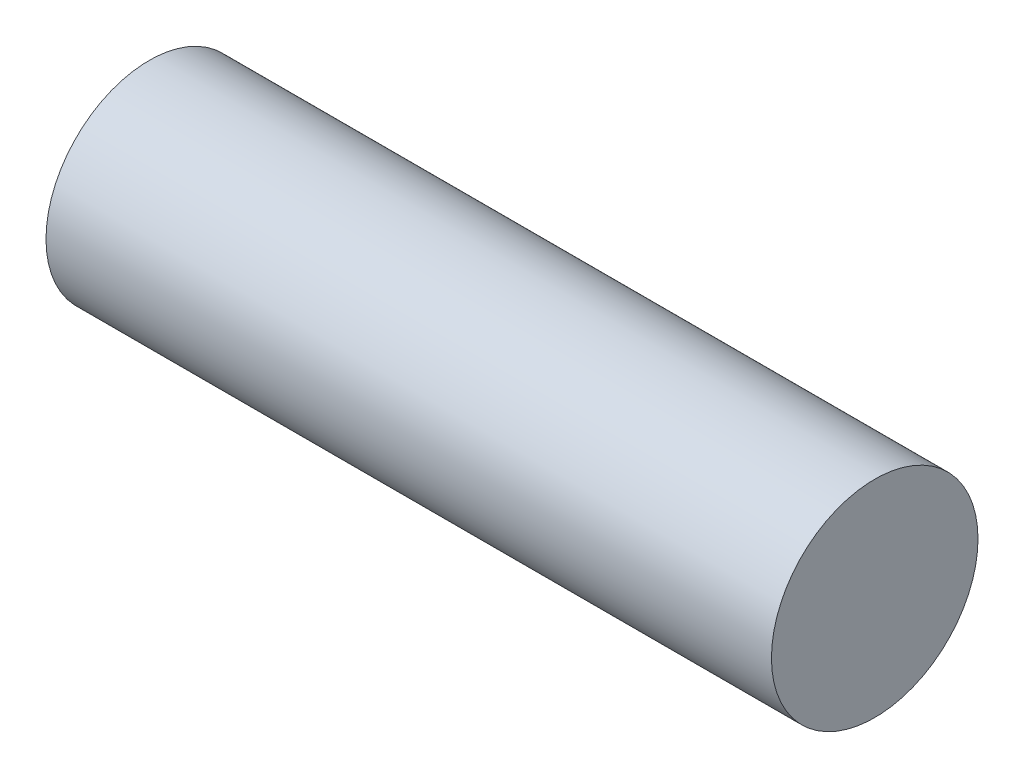
SolidWorks part; units mm, degrees
ref_plane "Front Plane" through (0, 0, 0) normal (0, 0, 1) x (1, 0, 0)
ref_plane "Top Plane" through (0, 0, 0) normal (0, 1, 0) x (1, 0, 0)
ref_plane "Right Plane" through (0, 0, 0) normal (1, 0, 0) x (0, 0, -1)
sketch "Sketch1" plane through (0, 0, 0) normal (1, 0, 0) x (0, 0, -1)
  circle A0 centre (0, 0) radius 10.25
  dimension "D1" = 20.5
extrude "Boss-Extrude1" add sketch "Sketch1" along normal blind 72
